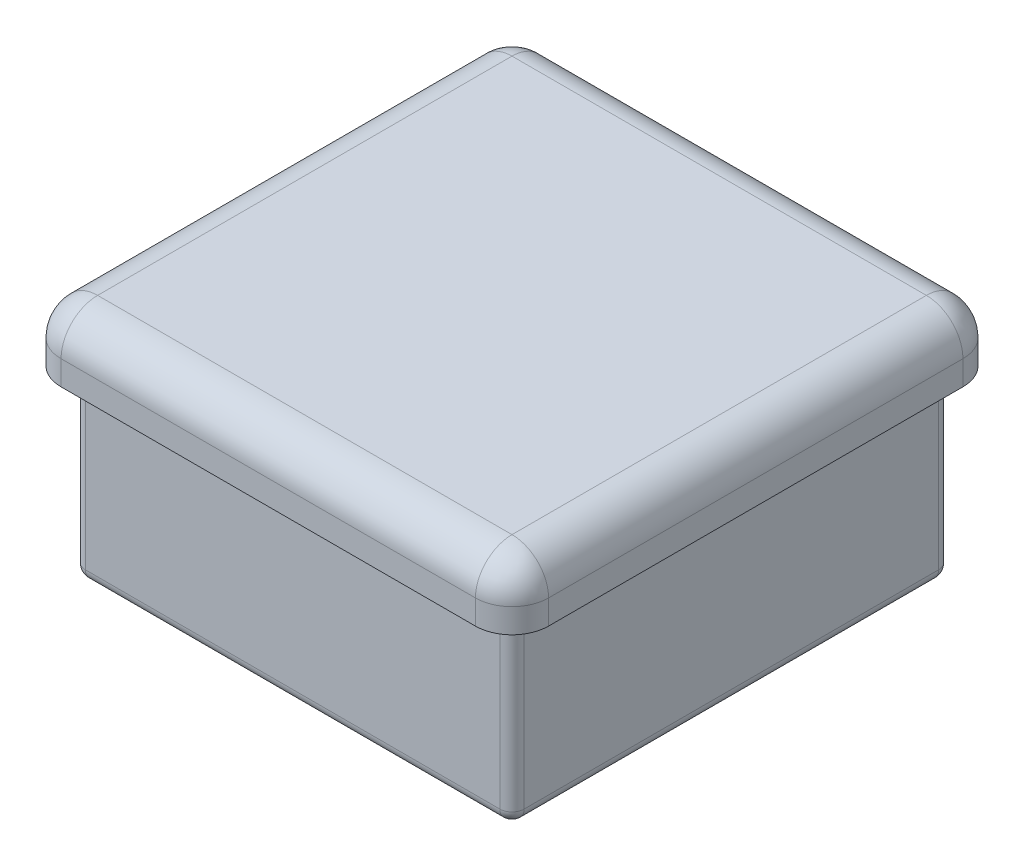
SolidWorks part; units mm, degrees
ref_plane "Plano frontal" through (0, 0, 0) normal (0, 0, 1) x (1, 0, 0)
ref_plane "Plano superior" through (0, 0, 0) normal (0, 1, 0) x (1, 0, 0)
ref_plane "Plano direito" through (0, 0, 0) normal (1, 0, 0) x (0, 0, -1)
sketch "Esboço1" plane through (0, 0, 0) normal (0, 1, 0) x (1, 0, 0)
  line L1 (20, -20) -> (-20, -20)
  line L2 (20, -20) -> (20, 20)
  line L3 (20, 20) -> (-20, 20)
  line L4 (-20, -20) -> (-20, 20)
  line L5 (20, -20) -> (-20, 20) construction
  line L6 (20, 20) -> (-20, -20) construction
  point P0 (0, 0)
  dimension "D1" = 40
  dimension "D2" = 40
extrude "Ressalto-extrusão1" add sketch "Esboço1" along normal mid plane 5
fillet "Filete1" radius 3 4 edges at (-20, 0, -20) (20, 0, -20) (-20, 0, 20) (20, 0, 20)
fillet "Filete2" radius 3 8 edges at (19.1213, 2.5, -19.1213) (20, 2.5, 0) (19.1213, 2.5, 19.1213) (0, 2.5, 20) (-19.1213, 2.5, 19.1213) (-20, 2.5, 0) (-19.1213, 2.5, -19.1213) (0, 2.5, -20)
sketch "Esboço2" plane through (0, -2.5, 0) normal (0, -1, 0) x (1, 0, 0)
  line L4 (-15.5, 15.5) -> (-15.5, -15.5)
  line L5 (-15.5, -15.5) -> (15.5, -15.5)
  line L6 (15.5, -15.5) -> (15.5, 15.5)
  line L7 (15.5, 15.5) -> (-15.5, 15.5)
  line L8 (-18, 17) -> (-18, -17)
  line L9 (-17, -18) -> (17, -18)
  line L10 (18, -17) -> (18, 17)
  line L11 (17, 18) -> (-17, 18)
  line L12 (-18, 17) -> (-18, -17)
  line L13 (-17, -18) -> (17, -18)
  line L14 (18, -17) -> (18, 17)
  line L15 (17, 18) -> (-17, 18)
  arc A4 (-15.5, -15.5) -> (-15.5, -15.5) centre (-15.5, -15.5) ccw
  arc A5 (15.5, -15.5) -> (15.5, -15.5) centre (15.5, -15.5) ccw
  arc A6 (15.5, 15.5) -> (15.5, 15.5) centre (15.5, 15.5) ccw
  arc A7 (-15.5, 15.5) -> (-15.5, 15.5) centre (-15.5, 15.5) ccw
  arc A8 (-18, -17) -> (-17, -18) centre (-17, -17) ccw
  arc A9 (17, -18) -> (18, -17) centre (17, -17) ccw
  arc A10 (18, 17) -> (17, 18) centre (17, 17) ccw
  arc A11 (-17, 18) -> (-18, 17) centre (-17, 17) ccw
  arc A12 (-18, -17) -> (-17, -18) centre (-17, -17) ccw
  arc A13 (17, -18) -> (18, -17) centre (17, -17) ccw
  arc A14 (18, 17) -> (17, 18) centre (17, 17) ccw
  arc A15 (-17, 18) -> (-18, 17) centre (-17, 17) ccw
  dimension "D1" = 2
  dimension "D2" = 2.5
extrude "Ressalto-extrusão2" add sketch "Esboço2" along normal blind 15
fillet "Filete3" radius 1 4 edges at (15.5, -10, -15.5) (-15.5, -10, -15.5) (15.5, -10, 15.5) (-15.5, -10, 15.5)
fillet "Filete4" radius 1 16 edges at (-15.2071, -17.5, -15.2071) (0, -17.5, -15.5) (15.2071, -17.5, -15.2071) (15.5, -17.5, 0) (15.2071, -17.5, 15.2071) (0, -17.5, 15.5) (-15.2071, -17.5, 15.2071) (-15.5, -17.5, 0) (0, -17.5, 18) (17.7071, -17.5, 17.7071) (18, -17.5, 0) (17.7071, -17.5, -17.7071) (0, -17.5, -18) (-17.7071, -17.5, -17.7071) (-18, -17.5, 0) (-17.7071, -17.5, 17.7071)
